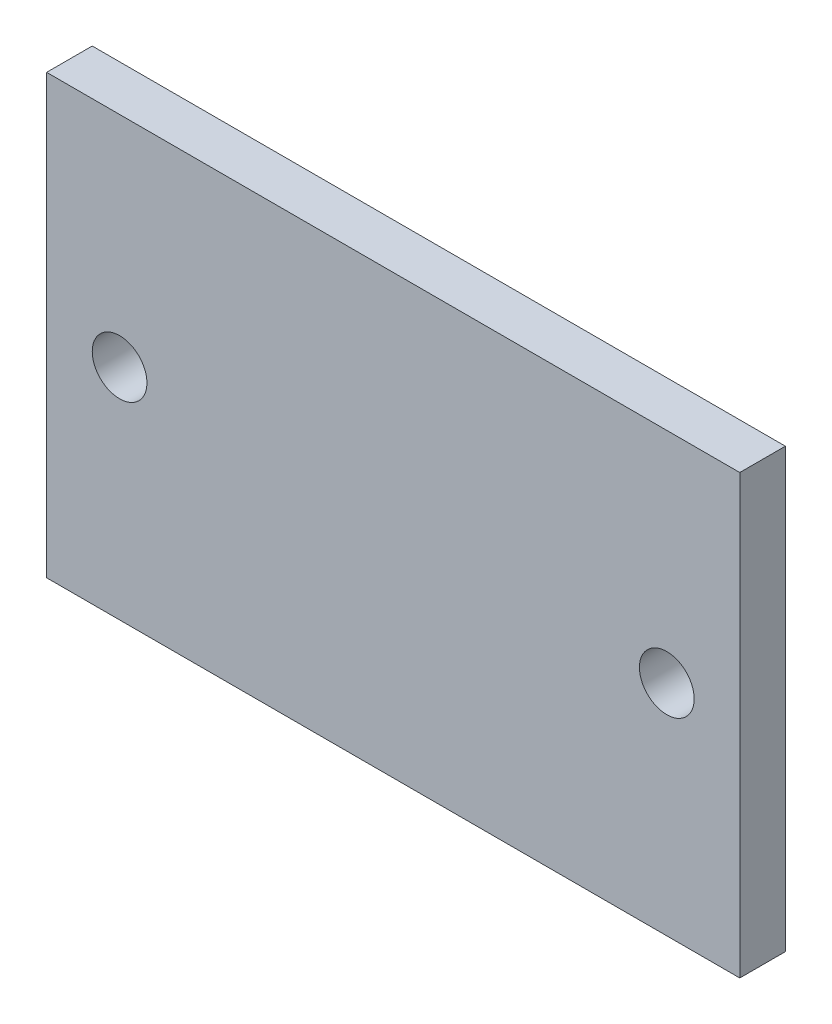
SolidWorks part; units mm, degrees
ref_plane "Front Plane" through (0, 0, 0) normal (0, 0, 1) x (1, 0, 0)
ref_plane "Top Plane" through (0, 0, 0) normal (0, 1, 0) x (1, 0, 0)
ref_plane "Right Plane" through (0, 0, 0) normal (1, 0, 0) x (0, 0, -1)
sketch "Sketch1" plane through (0, 0, 0) normal (0, 0, 1) x (1, 0, 0)
  line L1 (0, 0) -> (48.26, 0)
  line L2 (0, 0) -> (0, 30.48)
  line L3 (0, 30.48) -> (48.26, 30.48)
  line L4 (48.26, 0) -> (48.26, 30.48)
  dimension "D1" = 48.26
  dimension "D2" = 30.48
extrude "Boss-Extrude1" add sketch "Sketch1" along normal blind 3.175
sketch "Sketch2" plane through (0, 0, 0) normal (0, 0, -1) x (-1, 0, 0)
  circle A0 centre (-5.08, 15.24) radius 1.905 construction
  circle A1 centre (-43.18, 15.24) radius 1.905 construction
  circle A2 centre (-5.08, 15.24) radius 1.905
  circle A3 centre (-43.18, 15.24) radius 1.905
extrude "Cut-Extrude1" cut sketch "Sketch2" against normal blind 3.175
